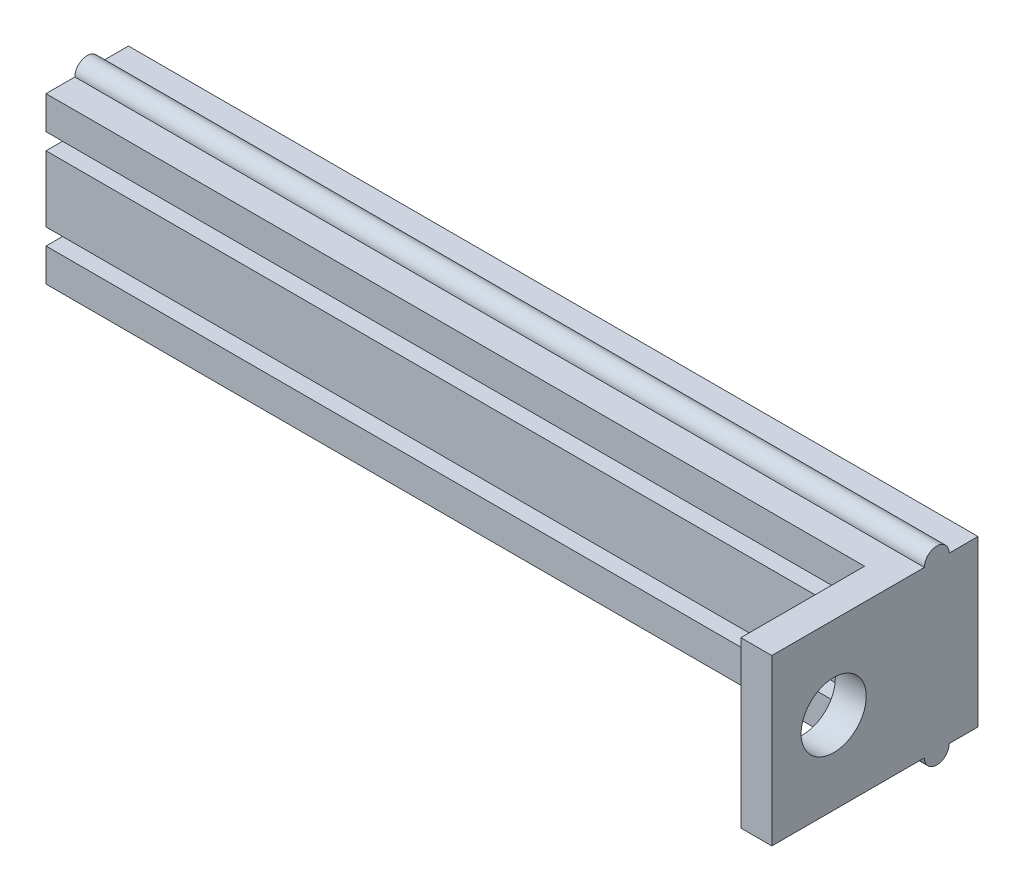
SolidWorks part; units mm, degrees
ref_plane "Front Plane" through (0, 0, 0) normal (0, 0, 1) x (1, 0, 0)
ref_plane "Top Plane" through (0, 0, 0) normal (0, 1, 0) x (1, 0, 0)
ref_plane "Right Plane" through (0, 0, 0) normal (1, 0, 0) x (0, 0, -1)
sketch "Sketch1" plane through (0, 0, 0) normal (0, 0, 1) x (1, 0, 0)
  line L1 (-103.3752, 68.6667) -> (102.6248, 68.6667)
  line L2 (-103.3752, 68.6667) -> (-103.3752, 28.6667)
  line L3 (-103.3752, 28.6667) -> (102.6248, 28.6667)
  line L4 (102.6248, 68.6667) -> (102.6248, 28.6667)
  dimension "D1" = 206
  dimension "D2" = 40
extrude "Boss-Extrude1" add sketch "Sketch1" along normal blind 20
sketch "Sketch2" plane through (0, 0, 20) normal (0, 0, 1) x (1, 0, 0)
  line L0 (-103.3752, 28.6667) -> (102.6248, 28.6667) construction
  line L1 (102.6248, 68.6667) -> (95.1248, 68.6667)
  line L2 (102.6248, 68.6667) -> (102.6248, 28.6667)
  line L3 (102.6248, 28.6667) -> (95.1248, 28.6667)
  line L4 (95.1248, 68.6667) -> (95.1248, 28.6667)
  dimension "D1" = 7.5
extrude "Boss-Extrude2" add sketch "Sketch2" along normal blind 30
sketch "Sketch4" plane through (-103.3752, 0, 0) normal (-1, 0, 0) x (0, 0, 1)
  line L0 (7, 68.6667) -> (13, 68.6667)
  line L1 (7, 28.6667) -> (13, 28.6667)
  arc A0 (13, 68.6667) -> (7, 68.6667) centre (10, 68.6667) ccw
  arc A1 (7, 28.6667) -> (13, 28.6667) centre (10, 28.6667) ccw
  dimension "D1" = 6
  dimension "D2" = 6
extrude "Boss-Extrude3" add sketch "Sketch4" against normal blind 206
sketch "Sketch6" plane through (-103.3752, 0, 0) normal (-1, 0, 0) x (0, 0, 1)
  line L0 (20, 68.6667) -> (20, 28.6667) construction
  line L1 (20, 60.6667) -> (15, 60.6667)
  line L2 (20, 60.6667) -> (20, 56.6667)
  line L3 (20, 56.6667) -> (15, 56.6667)
  line L6 (20, 68.6667) -> (13, 68.6667) construction
  line L7 (20, 40.6667) -> (15, 40.6667)
  line L8 (20, 40.6667) -> (20, 36.6667)
  line L9 (20, 36.6667) -> (15, 36.6667)
  line L11 (20, 28.6667) -> (13, 28.6667) construction
  line L12 (10, 63.6667) -> (10, 53.6667)
  line L13 (15, 56.6667) -> (15, 53.6667)
  line L14 (10, 63.6667) -> (15, 63.6667)
  line L15 (10, 63.6667) -> (10, 53.6667)
  line L16 (10, 53.6667) -> (15, 53.6667)
  line L17 (15, 63.6667) -> (15, 60.6667)
  line L18 (10, 43.6667) -> (15, 43.6667)
  line L19 (10, 43.6667) -> (10, 33.6667)
  line L20 (10, 33.6667) -> (15, 33.6667)
  line L21 (15, 43.6667) -> (15, 40.6667)
  line L22 (10, 43.6667) -> (10, 33.6667)
  line L24 (15, 36.6667) -> (15, 33.6667)
  point P27 (12.5, 63.6667)
  point P28 (12.5, 53.6667)
  line M24 (20, 28.6667) -> (20, 68.6667)
  dimension "D1" = 8
  dimension "D2" = 8
  dimension "D3" = 4
  dimension "D4" = 4
  dimension "D5" = 5
  dimension "D6" = 5
  dimension "D7" = 10
  dimension "D8" = 10
  dimension "D9" = 3
  dimension "D10" = 3
extrude "Cut-Extrude1" cut sketch "Sketch6" against normal blind 198.5 contours L17 L14 L12 L16 L13 L3 L1 M24 | L24 L9 L7 L21 L18 L19 L20 M24
sketch "Sketch7" plane through (95.1248, 0, 0) normal (-1, 0, 0) x (0, 0, 1)
  circle A0 centre (35, 48.6667) radius 7.9
  point P6 (35, 48.6667)
  dimension "D1" = 15.8
extrude "Cut-Extrude2" cut sketch "Sketch7" against normal through all
